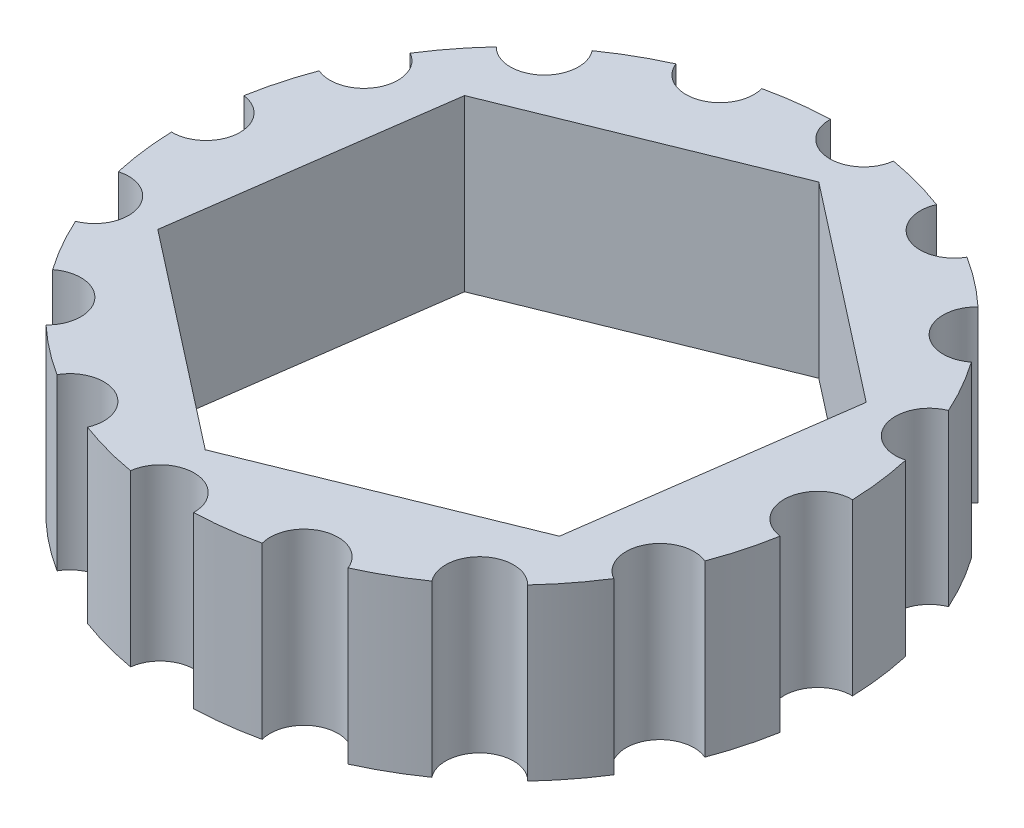
SolidWorks part; units mm, degrees
ref_plane "Front Plane" through (0, 0, 0) normal (0, 0, 1) x (1, 0, 0)
ref_plane "Top Plane" through (0, 0, 0) normal (0, 1, 0) x (1, 0, 0)
ref_plane "Right Plane" through (0, 0, 0) normal (1, 0, 0) x (0, 0, -1)
sketch "Sketch1" plane through (0, 0, 0) normal (0, 1, 0) x (1, 0, 0)
  line L0 (0, 0) -> (0, 10) construction
  line L1 (-10, -10) -> (10, -10)
  line L2 (-10, -10) -> (-10, 10)
  line L3 (-10, 10) -> (10, 10)
  line L4 (10, -10) -> (10, 10)
  line L5 (-10, -10) -> (10, 10) construction
  line L6 (-10, 10) -> (10, -10) construction
  line L7 (0, 10) -> (22.5, 10) construction
  line L8 (22.5, 10) -> (-22.5, 10)
  line L9 (-22.5, 10) -> (-22.5, 70)
  line L10 (-22.5, 70) -> (22.5, 70)
  line L11 (22.5, 70) -> (22.5, 10)
  line L12 (-22.5, 10) -> (-10, -10)
  line L13 (22.5, 10) -> (10, -10) construction
  line L14 (10, -10) -> (22.5, 10)
  line L15 (-10, -10) -> (10, -10)
  line L16 (-10, -10) -> (-10, -20)
  line L17 (-10, -20) -> (10, -20)
  line L18 (10, -10) -> (10, -20)
  circle A0 centre (0, 0) radius 4
extrude "Boss-Extrude2" add sketch "Sketch1" along normal blind 2 contours L11 L10 L9 L8 L3 | L8 L12 L2 | L4 L14 L8 | L1 L4 L3 L2 A0 | A0 | L18 L1 L16 L17
sketch "Sketch2" plane through (0, 2, 0) normal (0, 1, 0) x (1, 0, 0)
  line L0 (-21.5, 69) -> (-21.5, 11)
  line L1 (-22.5, 70) -> (22.5, 70)
  line L2 (-22.5, 70) -> (-22.5, 10)
  line L3 (-22.5, 10) -> (22.5, 10)
  line L4 (22.5, 70) -> (22.5, 10)
  line L5 (-21.5, 11) -> (21.5, 11)
  line L6 (21.5, 69) -> (21.5, 11)
  line L7 (-21.5, 69) -> (21.5, 69)
  dimension "D1" = 1
extrude "Boss-Extrude3" add sketch "Sketch2" along normal blind 4
sketch "Sketch6" plane through (0, 2, 0) normal (0, 1, 0) x (1, 0, 0)
  line L0 (-10, -20) -> (-24.7467, -20) construction
  line L1 (-22.5, 10) -> (-22.5, -20) construction
  line L2 (22.5, 10) -> (22.5, -20) construction
  line L3 (22.5, -20) -> (10, -20) construction
  line L5 (-22.5, 10) -> (22.5, 10)
  line L6 (-22.5, 10) -> (-22.5, -20)
  line L7 (-22.5, -20) -> (22.5, -20)
  line L8 (22.5, 10) -> (22.5, -20)
extrude "Boss-Extrude4" add sketch "Sketch6" against normal up to surface (2 mm away) up to face at (0, 0, -12.5)
sketch "Sketch7" plane through (0, 2, 0) normal (0, 1, 0) x (1, 0, 0)
  line L1 (0, 0) -> (0, -2) construction
  line L3 (-9.5, 9.5) -> (9.5, 9.5)
  line L4 (-9.5, 9.5) -> (-9.5, -9.5)
  line L5 (-9.5, -9.5) -> (9.5, -9.5)
  line L6 (9.5, 9.5) -> (9.5, -9.5)
  line L7 (-9.5, 9.5) -> (9.5, -9.5) construction
  line L8 (-9.5, -9.5) -> (9.5, 9.5) construction
  circle A0 centre (0, -1) radius 10
extrude "Cut-Extrude4" cut sketch "Sketch7" against normal blind 4 contours A0 L6 L3 L4 | A0 L4 L5 | A0 L5 L6
sketch "Sketch8" plane through (0, 2, 0) normal (0, 1, 0) x (1, 0, 0)
  line L53 (9.5, 2.1225) -> (9.5, 9.5)
  line L54 (9.5, 9.5) -> (-9.5, 9.5)
  line L55 (-9.5, 9.5) -> (-9.5, 2.1225)
  line L56 (9.5, 2.1225) -> (9.5, 9.5)
  line L57 (9.5, 9.5) -> (-9.5, 9.5)
  line L58 (-9.5, 9.5) -> (-9.5, 2.1225)
  line L60 (-9.5, -9.5) -> (-5.2678, -9.5)
  line L61 (-9.5, -4.1225) -> (-9.5, -9.5)
  line L62 (-9.5, -9.5) -> (-5.2678, -9.5)
  line L63 (-9.5, -4.1225) -> (-9.5, -9.5)
  line L66 (9.5, -9.5) -> (9.5, -4.1225)
  line L67 (5.2678, -9.5) -> (9.5, -9.5)
  line L68 (9.5, -9.5) -> (9.5, -4.1225)
  line L69 (5.2678, -9.5) -> (9.5, -9.5)
  arc A20 (9.5, 2.1225) -> (-9.5, 2.1225) centre (0, -1) ccw
  arc A21 (9.5, 2.1225) -> (-9.5, 2.1225) centre (0, -1) ccw
  arc A23 (-9.5, -4.1225) -> (-5.2678, -9.5) centre (0, -1) ccw
  arc A24 (-9.5, -4.1225) -> (-5.2678, -9.5) centre (0, -1) ccw
  arc A26 (5.2678, -9.5) -> (9.5, -4.1225) centre (0, -1) ccw
  arc A27 (5.2678, -9.5) -> (9.5, -4.1225) centre (0, -1) ccw
  dimension "D1" = 0
  dimension "D2" = 0
  dimension "D3" = 0
extrude "Boss-Extrude5" add sketch "Sketch8" along normal blind 7 separate body
sketch "Sketch14" plane through (0, 0, 0) normal (0, -1, 0) x (1, 0, 0)
  line L0 (0, 0) -> (0, 1) construction
  circle A1 centre (0, 1) radius 4
extrude "Cut-Extrude7" cut sketch "Sketch14" against normal blind 19
sketch "Sketch20" plane through (0, 2, 0) normal (0, 1, 0) x (1, 0, 0)
  line L0 (-13.5553, -10.8363) -> (-12.9295, -10.8363) construction
  line L2 (0, 0) -> (0, -1) construction
  line L3 (0, -1) -> (7.1604, -4.5677) construction
  line L5 (7.1604, -4.5677) -> (7.5859, 1.5404)
  line L6 (7.5859, 1.5404) -> (3.5677, 6.1604)
  line L7 (3.5677, 6.1604) -> (-2.5404, 6.5859)
  line L8 (-2.5404, 6.5859) -> (-7.1604, 2.5677)
  line L9 (-7.1604, 2.5677) -> (-7.5859, -3.5404)
  line L10 (-7.5859, -3.5404) -> (-3.5677, -8.1604)
  line L11 (-3.5677, -8.1604) -> (2.5404, -8.5859)
  line L12 (2.5404, -8.5859) -> (7.1604, -4.5677)
  circle A1 centre (0, -1) radius 7.391 construction
  circle A3 centre (0, -1) radius 9.7
extrude "Boss-Extrude6" add sketch "Sketch20" along normal blind 5
sketch "Sketch21" plane through (0, 9, 0) normal (0, 1, 0) x (1, 0, 0)
  line L6 (-9.5, 9.5) -> (-9.5, 2.1225)
  line L7 (9.5, 2.1225) -> (9.5, 9.5)
  line L8 (9.5, 9.5) -> (-9.5, 9.5)
  line L9 (-9.5, 9.5) -> (-9.5, 2.1225)
  line L10 (9.5, 2.1225) -> (9.5, 9.5)
  line L11 (9.5, 9.5) -> (-9.5, 9.5)
  arc A2 (9.5, 2.1225) -> (-9.5, 2.1225) centre (0, -1) ccw
  arc A3 (9.5, 2.1225) -> (-9.5, 2.1225) centre (0, -1) ccw
  dimension "D1" = 0
extrude "Cut-Extrude8" cut sketch "Sketch21" against normal blind 15
sketch "Sketch22" plane through (0, 9, 0) normal (0, 1, 0) x (1, 0, 0)
  line L4 (-9.5, -4.1225) -> (-9.5, -9.5)
  line L5 (-9.5, -9.5) -> (-5.2678, -9.5)
  line L6 (-9.5, -4.1225) -> (-9.5, -9.5)
  line L7 (-9.5, -9.5) -> (-5.2678, -9.5)
  arc A2 (-9.5, -4.1225) -> (-5.2678, -9.5) centre (0, -1) ccw
  arc A3 (-9.5, -4.1225) -> (-5.2678, -9.5) centre (0, -1) ccw
  dimension "D1" = 0
extrude "Cut-Extrude9" cut sketch "Sketch22" against normal blind 15
sketch "Sketch23" plane through (0, 9, 0) normal (0, 1, 0) x (1, 0, 0)
  line L4 (5.2678, -9.5) -> (9.5, -9.5)
  line L5 (9.5, -9.5) -> (9.5, -4.1225)
  line L6 (5.2678, -9.5) -> (9.5, -9.5)
  line L7 (9.5, -9.5) -> (9.5, -4.1225)
  arc A2 (5.2678, -9.5) -> (9.5, -4.1225) centre (0, -1) ccw
  arc A3 (5.2678, -9.5) -> (9.5, -4.1225) centre (0, -1) ccw
  dimension "D1" = 0
extrude "Cut-Extrude10" cut sketch "Sketch23" against normal blind 31
sketch "Sketch24" plane through (0, 2, 0) normal (0, 1, 0) x (1, 0, 0)
  line L1 (-22.5, 10) -> (22.5, 10)
  line L2 (-22.5, 10) -> (-22.5, -20)
  line L3 (-22.5, -20) -> (22.5, -20)
  line L4 (22.5, 10) -> (22.5, -20)
extrude "Cut-Extrude11" cut sketch "Sketch24" against normal blind 31
sketch "Sketch25" plane through (0, 6, 0) normal (0, 1, 0) x (1, 0, 0)
  line L8 (-22.5, 70) -> (-22.5, 10)
  line L9 (-22.5, 10) -> (22.5, 10)
  line L10 (22.5, 10) -> (22.5, 70)
  line L11 (22.5, 70) -> (-22.5, 70)
  line L12 (-22.5, 70) -> (-22.5, 10)
  line L13 (-22.5, 10) -> (22.5, 10)
  line L14 (22.5, 10) -> (22.5, 70)
  line L15 (22.5, 70) -> (-22.5, 70)
  dimension "D1" = 0
extrude "Cut-Extrude12" cut sketch "Sketch25" against normal blind 31
sketch "Sketch26" plane through (0, 7, 0) normal (0, 1, 0) x (1, 0, 0)
  line L0 (-7.1604, 2.5677) -> (7.1604, -4.5677) construction
  line L1 (7.1604, -4.5677) -> (9.8028, -5.8843) construction
  line L2 (9.8028, -5.8843) -> (-13.1891, 5.5715) construction
  line L3 (-2.5404, 6.5859) -> (2.5404, -8.5859) construction
  line L4 (2.5404, -8.5859) -> (3.263, -10.7438) construction
  line L5 (3.263, -10.7438) -> (-3.7902, 10.3179) construction
  line L6 (3.5677, 6.1604) -> (-3.5677, -8.1604) construction
  line L7 (-3.5677, -8.1604) -> (-6.3978, -13.8404) construction
  line L8 (-6.3978, -13.8404) -> (5.4855, 10.0094) construction
  line L9 (-7.5859, -3.5404) -> (7.5859, 1.5404) construction
  line L10 (7.5859, 1.5404) -> (13.9245, 3.6631) construction
  line L11 (13.9245, 3.6631) -> (-12.9974, -5.3526) construction
  line L12 (-9.1979, -4.0803) -> (-8.682, 3.3259) construction
  line L13 (-8.682, 3.3259) -> (-3.0803, 8.1979) construction
  line L14 (-3.0803, 8.1979) -> (4.3259, 7.682) construction
  line L15 (4.3259, 7.682) -> (9.1979, 2.0803) construction
  line L16 (9.1979, 2.0803) -> (8.682, -5.3259) construction
  line L17 (8.682, -5.3259) -> (3.0803, -10.1979) construction
  line L18 (3.0803, -10.1979) -> (-4.3259, -9.682) construction
  line L19 (-4.3259, -9.682) -> (-9.1979, -4.0803) construction
  line L20 (0, -1) -> (10.286, 7.9462) construction
  line L21 (0, -1) -> (13.6743, -1.9526) construction
  line L22 (0, -1) -> (8.1556, -10.377) construction
  line L23 (8.1556, -10.377) -> (-8.682, 8.9822) construction
  line L24 (0, -1) -> (-11.5779, -0.1934) construction
  line L25 (0, -1) -> (-5.5768, -5.8504) construction
  line L26 (-7.5859, -3.5404) -> (-3.5677, -8.1604) construction
  line L27 (-5.5768, -5.8504) -> (-9.1979, -8.9999) construction
  line L28 (0, -1) -> (-0.6228, -9.94) construction
  line L29 (-0.6228, -9.94) -> (-0.8544, -13.2639) construction
  line L30 (0, -1) -> (0.7885, 10.3179) construction
  circle A0 centre (0, -1) radius 9.7 construction
  circle A1 centre (0.6741, 8.6765) radius 1
  circle A2 centre (-6.3657, 6.319) radius 1
  circle A3 centre (-9.6765, -0.3259) radius 1
  circle A4 centre (-8.682, 3.3259) radius 1
  circle A5 centre (-9.1979, -4.0803) radius 1
  circle A6 centre (-7.319, -7.3657) radius 1
  circle A7 centre (-4.3259, -9.682) radius 1
  circle A8 centre (-0.6741, -10.6765) radius 1
  circle A9 centre (3.0803, -10.1979) radius 1
  circle A10 centre (6.3657, -8.319) radius 1
  circle A11 centre (8.682, -5.3259) radius 1
  circle A12 centre (9.6765, -1.6741) radius 1
  circle A13 centre (9.1979, 2.0803) radius 1
  circle A14 centre (7.319, 5.3657) radius 1
  circle A15 centre (4.3259, 7.682) radius 1
  circle A16 centre (-3.0803, 8.1979) radius 1
extrude "Cut-Extrude14" cut sketch "Sketch26" against normal blind 31
sketch "Sketch28" plane through (0, 7, 0) normal (0, 1, 0) x (1, 0, 0)
  line L1 (2.5404, -8.5859) -> (-2.5404, 6.5859) construction
  circle A0 centre (0, -1) radius 8.3309
extrude "Boss-Extrude7" add sketch "Sketch28" against normal up to surface (5 mm away) up to face at (0, 2, 1)
sketch "Sketch29" plane through (0, 7, 0) normal (0, 1, 0) x (1, 0, 0)
  line L0 (-0.6046, -9.679) -> (0.6046, 7.679) construction
  line L1 (0, -1) -> (-6.3112, 3.9162) construction
  line L3 (-6.3112, 3.9162) -> (-7.4131, -4.0076)
  line L4 (-7.4131, -4.0076) -> (-1.1019, -8.9237)
  line L5 (-1.1019, -8.9237) -> (6.3112, -5.9162)
  line L6 (6.3112, -5.9162) -> (7.4131, 2.0076)
  line L7 (7.4131, 2.0076) -> (1.1019, 6.9237)
  line L8 (1.1019, 6.9237) -> (-6.3112, 3.9162)
  arc A0 (0.3257, -10.6945) -> (-1.6668, -10.5557) centre (-0.6741, -10.6765) ccw construction
  arc A1 (-0.3257, 8.6945) -> (1.6668, 8.5557) centre (0.6741, 8.6765) ccw construction
  circle A2 centre (0, -1) radius 6.9282 construction
extrude "Cut-Extrude15" cut sketch "Sketch29" against normal blind 10
